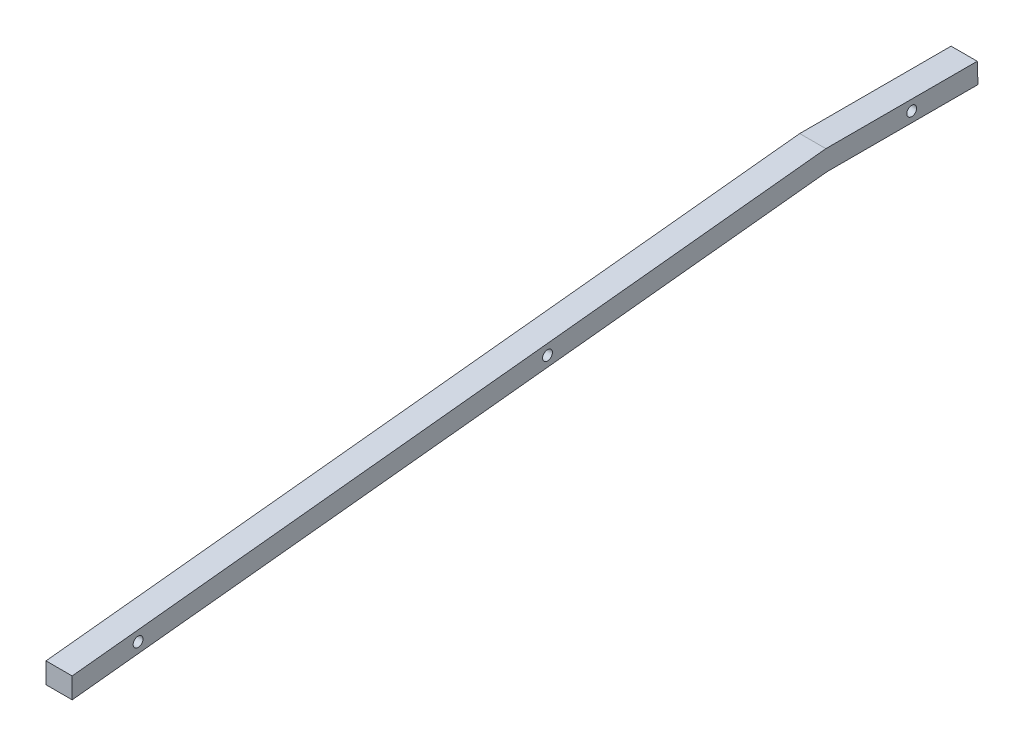
SolidWorks part; units mm, degrees
material "Acrylic (Medium-high impact)"
ref_plane "Front Plane" through (0, 0, 0) normal (0, 0, 1) x (1, 0, 0)
ref_plane "Top Plane" through (0, 0, 0) normal (0, 1, 0) x (1, 0, 0)
ref_plane "Right Plane" through (0, 0, 0) normal (1, 0, 0) x (0, 0, -1)
sketch "Sketch8" plane through (0, 0, 0) normal (1, 0, 0) x (0, 0, -1)
  line L0 (-84.4844, -6.1593) -> (-84.4844, -11.1872)
  line L2 (-84.4844, -6.1593) -> (98.4505, 13.2099)
  line L3 (98.4505, 13.2099) -> (135.1962, 13.2109)
  line L4 (-84.4844, -11.1872) -> (98.7868, 8.2175)
  line L5 (98.7868, 8.2175) -> (135.3786, 8.2109)
  line L9 (135.1962, 13.2109) -> (135.3786, 8.2109)
  point P6 (119.2768, 10.7105)
  point P7 (-68.4844, -6.9792)
  point P8 (30.8895, 3.5425)
  dimension "D1" = 2.5
  dimension "D2" = 16
  dimension "D3" = 2.5
  dimension "D4" = 5
  dimension "D5" = 16
  dimension "D6" = 2.5
  dimension "D7" = 5
extrude "Boss-Extrude1" add sketch "Sketch8" along normal blind 6.35 separate body
hole_wizard "3/32 (0.09375) Diameter Hole1" positions "Sketch12" profile "Sketch11" hole size "3/32" standard "ANSI Inch"
sketch "Sketch12" plane through (6.35, 0, 0) normal (1, 0, 0) x (0, 0, -1)
  point P0 (-68.4844, -6.9792)
  point P3 (30.8895, 3.5425)
  point P6 (119.2768, 10.7105)
sketch "Sketch11" plane through (6.35, -6.9792, 68.4844) normal (0, 1, 0) x (0, 0, -1)
  line L0 (0, 0) -> (0, 8.7154)
  line L1 (0, 8.7154) -> (1.1906, 8)
  line L2 (1.1906, 8) -> (1.1906, 0)
  line L5 (1.1906, 0) -> (0, 0)
  line L10 (0, 8.7154) -> (-1.1906, 8) construction
  line L11 (0, -6.35) -> (0, 107.95) construction
  dimension "Hole Dia." = 2.3812
  dimension "Hole Depth" = 8
  dimension "Drill Angle" = 118
